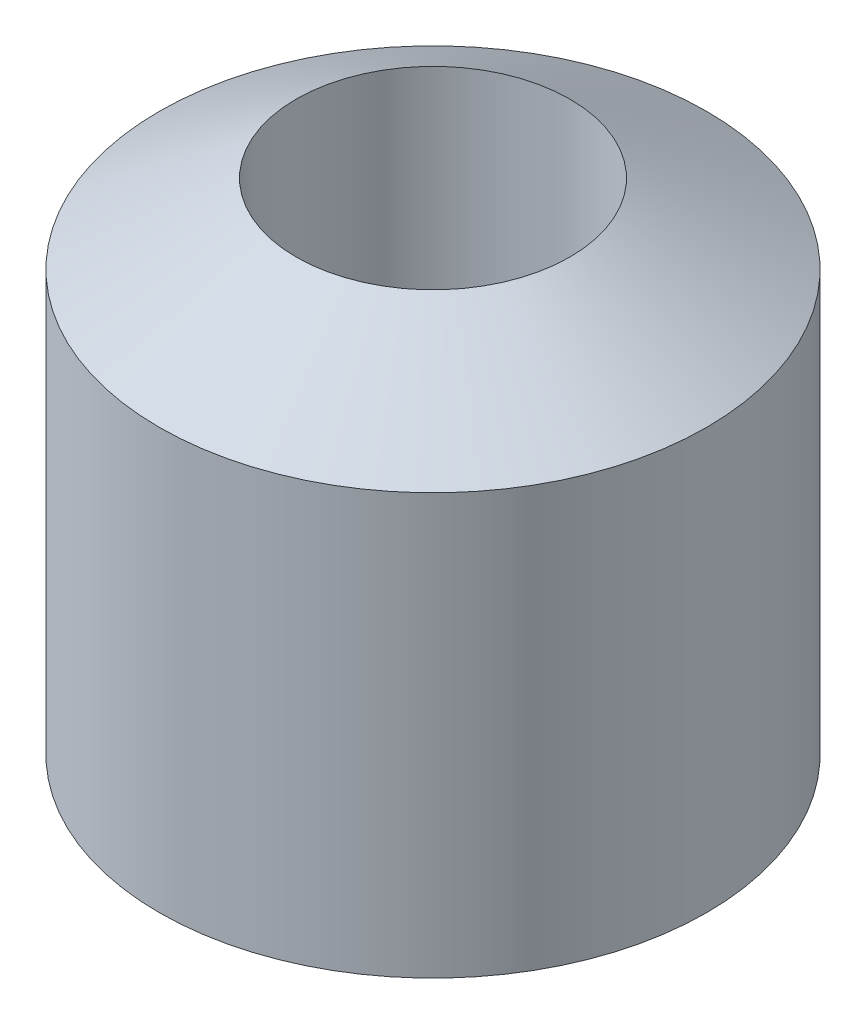
SolidWorks part; units mm, degrees
ref_plane "Front Plane" through (0, 0, 0) normal (0, 0, 1) x (1, 0, 0)
ref_plane "Top Plane" through (0, 0, 0) normal (0, 1, 0) x (1, 0, 0)
ref_plane "Right Plane" through (0, 0, 0) normal (1, 0, 0) x (0, 0, -1)
sketch "Sketch1" plane through (0, 0, 0) normal (1, 0, 0) x (0, 0, -1)
  line L0 (0, 129.3308) -> (0, -139.2538) construction
  line L1 (-102.5385, 0) -> (261.3077, 0) construction
  line L2 (14, -29.5829) -> (14, 29.5829)
  line L3 (28, -21.5) -> (28, 21.5)
  line L4 (14, 29.5829) -> (28, 21.5)
  line L5 (14, -29.5829) -> (28, -21.5)
  point P10 (28, 0)
  point P11 (14, 0)
  dimension "D1" = 60
  dimension "D2" = 14
  dimension "D3" = 28
  dimension "D4" = 43
revolve "Revolve1" add sketch "Sketch1" angle 360 about L0
